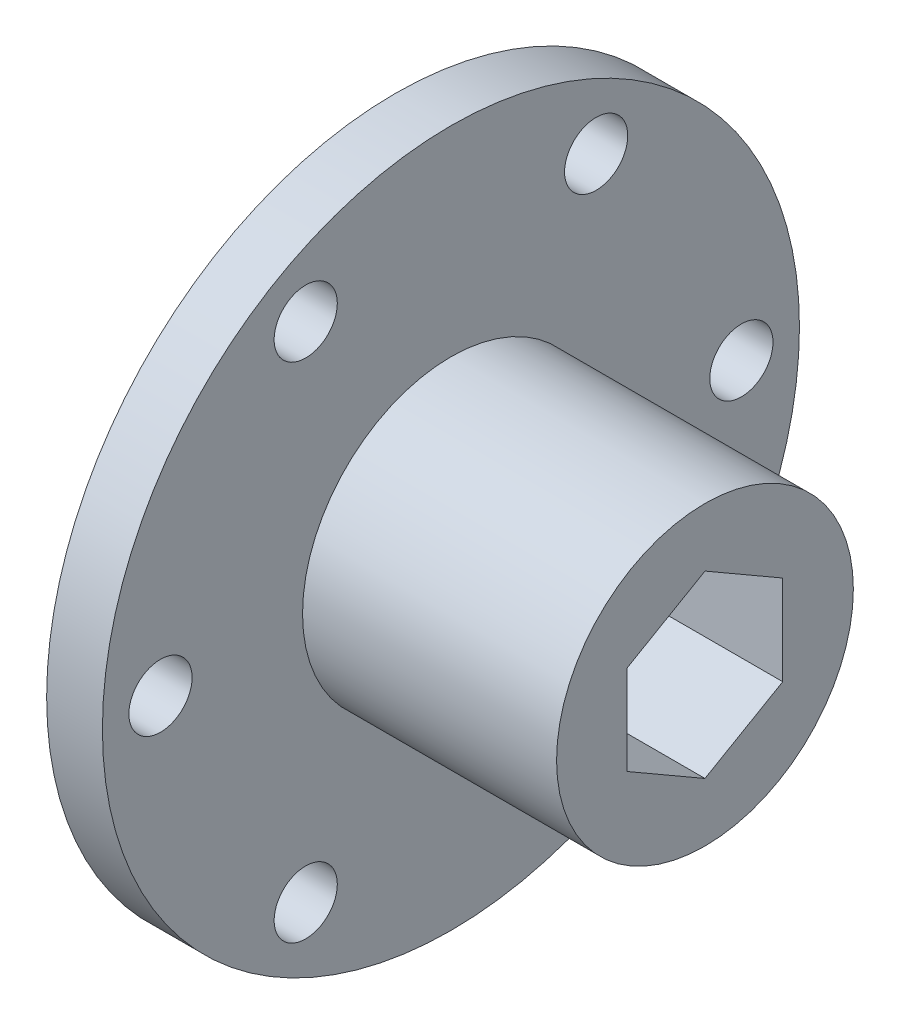
SolidWorks part; units mm, degrees
ref_plane "Front Plane" through (0, 0, 0) normal (0, 0, 1) x (1, 0, 0)
ref_plane "Top Plane" through (0, 0, 0) normal (0, 1, 0) x (1, 0, 0)
ref_plane "Right Plane" through (0, 0, 0) normal (1, 0, 0) x (0, 0, -1)
sketch "Sketch1" plane through (0, 0, 0) normal (0, 0, 1) x (1, 0, 0)
  line L0 (-17.6071, 28.575) -> (-17.6071, 0)
  line L1 (-17.6071, 0) -> (-13.0351, 0)
  line L2 (-13.0351, 0) -> (-13.0351, 28.575)
  line L3 (-13.0351, 28.575) -> (-17.6071, 28.575)
  line L4 (-17.6071, 0) -> (-13.0351, 0) construction
revolve "Revolve1" add sketch "Sketch1" angle 360 about L4
sketch "Sketch2" plane through (-13.0351, 0, 0) normal (1, 0, 0) x (0, 0, -1)
  circle A0 centre (0, 0) radius 12.1666
extrude "Boss-Extrude1" add sketch "Sketch2" along normal blind 20.828
sketch "Sketch3" plane through (-17.6071, 0, 0) normal (-1, 0, 0) x (0, 0, 1)
  line L0 (0, -7.3617) -> (6.3754, -3.6809)
  line L1 (6.3754, -3.6809) -> (6.3754, 3.6808)
  line L2 (6.3754, 3.6808) -> (0, 7.3617)
  line L3 (0, 7.3617) -> (-6.3754, 3.6808)
  line L4 (-6.3754, 3.6808) -> (-6.3754, -3.6809)
  line L5 (-6.3754, -3.6809) -> (0, -7.3617)
extrude "Cut-Extrude1" cut sketch "Sketch3" against normal through all
hole_wizard "Hole1" positions "Sketch5" profile "Sketch4" legacy
sketch "Sketch5" plane through (-17.6071, 0, 0) normal (-1, 0, 0) x (0, 0, 1)
  point P0 (11.9062, -20.6222)
  point P1 (-11.9062, -20.6222)
  point P2 (-23.8125, 0)
  point P3 (-11.9062, 20.6222)
  point P4 (11.9062, 20.6222)
  point P5 (23.8125, 0)
sketch "Sketch4" plane through (-17.6071, -20.6222, 11.9062) normal (0, 1, 0) x (0, 0, 1)
  line L0 (0, 0) -> (0, 25.4)
  line L1 (0, 25.4) -> (2.5908, 25.4)
  line L2 (2.5908, 25.4) -> (2.5908, 0)
  line L3 (2.5908, 0) -> (0, 0)
  line L4 (0, 110) -> (0, -10) construction
  dimension "Diameter" = 5.1816
  dimension "Depth" = 25.4
